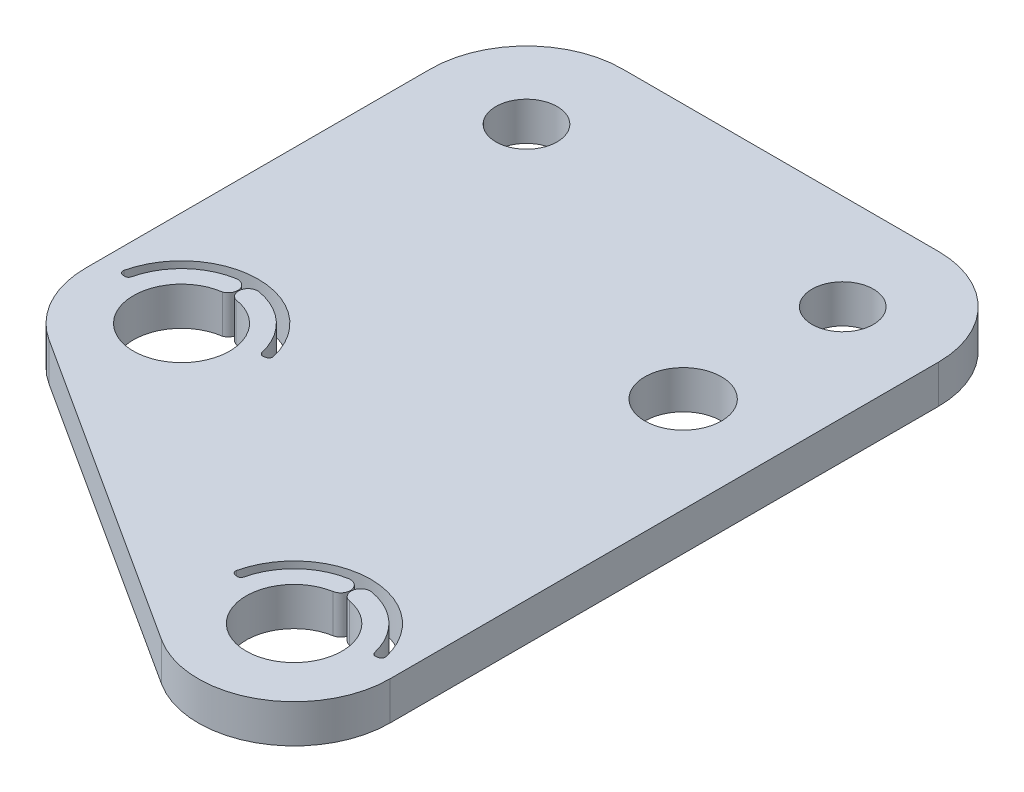
SolidWorks part; units mm, degrees
ref_plane "Front" through (0, 0, 0) normal (0, 0, 1) x (1, 0, 0)
ref_plane "Top" through (0, 0, 0) normal (0, 1, 0) x (1, 0, 0)
ref_plane "Right" through (0, 0, 0) normal (1, 0, 0) x (0, 0, -1)
sketch "Sketch1" plane through (0, 0, 0) normal (0, 1, 0) x (1, 0, 0)
  line L0 (0, 0) -> (26.5, 0)
  line L1 (26.5, 0) -> (26.5, -42.7917)
  line L2 (26.5, -42.7917) -> (0, -25.7273)
  line L3 (0, -25.7273) -> (0, 0)
  line L4 (5, -5) -> (21.5, -5) construction
  line L5 (21.5, -5) -> (21.5, -33.625) construction
  line L6 (21.5, -33.625) -> (5, -23) construction
  line L7 (5, -23) -> (5, -5) construction
  circle A0 centre (5, -23) radius 2.51
  circle A1 centre (21.5, -33.625) radius 2.5
  circle A2 centre (21.5, -5) radius 1.6
  circle A3 centre (5, -5) radius 1.6
  circle A4 centre (21.5, -13.325) radius 2
  dimension "D8" = 5.02
  dimension "D9" = 3.2
  dimension "D10" = 5
  dimension "D12" = 4
  dimension "D1" = 16.5
  dimension "D3" = 5
  dimension "D4" = 5
  dimension "D5" = 5
  dimension "D6" = 5
  dimension "D7" = 18
  dimension "D2" = 10.625
  dimension "D11" = 8.325
extrude "Boss-Extrude1" add sketch "Sketch1" along normal blind 2
fillet "Fillet1" radius 5 4 edges at (26.5, 1, 0) (0, 1, 0) (0, 1, 25.7273) (26.5, 1, 42.7917)
other "Move Face1" [suppressed] parameters "D1"=0.0762
sketch "Sketch2" plane through (0, 2, 0) normal (0, 1, 0) x (1, 0, 0)
  point P0 (5, -23)
  line B0 (17.8615, -32.9834) -> (17.7629, -32.9661)
  line B1 (25.1385, -32.9834) -> (25.2371, -32.9661)
  arc B2 (17.6028, -32.724) -> (25.3972, -32.724) centre (21.5, -33.625) cw
  arc B3 (21.0659, -31.163) -> (20.8922, -30.1782) centre (20.9791, -30.6706) ccw
  arc B4 (20.8922, -30.1782) -> (18.0911, -32.8318) centre (21.5, -33.625) ccw
  arc B5 (22.1078, -30.1782) -> (24.9089, -32.8318) centre (21.5, -33.625) cw
  arc B6 (21.9341, -31.163) -> (22.1078, -30.1782) centre (22.0209, -30.6706) cw
  arc B7 (21.0659, -31.163) -> (21.9341, -31.163) centre (21.5, -33.625) cw
  arc B8 (17.8615, -32.9834) -> (18.0911, -32.8318) centre (17.8963, -32.7865) ccw
  arc B9 (17.7629, -32.9661) -> (17.6028, -32.724) centre (17.7976, -32.7691) cw
  arc B10 (25.2371, -32.9661) -> (25.3972, -32.724) centre (25.2024, -32.7691) ccw
  arc B11 (25.1385, -32.9834) -> (24.9089, -32.8318) centre (25.1037, -32.7865) cw
  line B12 (1.3615, -22.3584) -> (1.2629, -22.3411)
  line B13 (8.6385, -22.3584) -> (8.7371, -22.3411)
  arc B14 (1.1028, -22.099) -> (8.8972, -22.099) centre (5, -23) cw
  arc B15 (4.5659, -20.538) -> (4.3922, -19.5532) centre (4.4791, -20.0456) ccw
  arc B16 (4.3922, -19.5532) -> (1.5911, -22.2068) centre (5, -23) ccw
  arc B17 (5.6078, -19.5532) -> (8.4089, -22.2068) centre (5, -23) cw
  arc B18 (5.4341, -20.538) -> (5.6078, -19.5532) centre (5.5209, -20.0456) cw
  arc B19 (4.5659, -20.538) -> (5.4341, -20.538) centre (5, -23) cw
  arc B20 (1.3615, -22.3584) -> (1.5911, -22.2068) centre (1.3963, -22.1615) ccw
  arc B21 (1.2629, -22.3411) -> (1.1028, -22.099) centre (1.2976, -22.1441) cw
  arc B22 (8.7371, -22.3411) -> (8.8972, -22.099) centre (8.7024, -22.1441) ccw
  arc B23 (8.6385, -22.3584) -> (8.4089, -22.2068) centre (8.6037, -22.1615) cw
sketch_block_instance "5mm_bore_flexure_relief-1"
sketch_block "5mm_bore_flexure_relief" parameters "D4"=2.5, "D6"=0.2, "D1"=80, "D2"=0.5, "D3"=70, "D5"=1
sketch_block_instance "5mm_bore_flexure_relief-2"
extrude "Cut-Extrude2" cut sketch "Sketch2" against normal through all
equation "\"D4@Sketch1\"=\"D3@Sketch1\""
equation "\"D5@Sketch1\"=\"D3@Sketch1\""
equation "\"D6@Sketch1\"=\"D3@Sketch1\""
